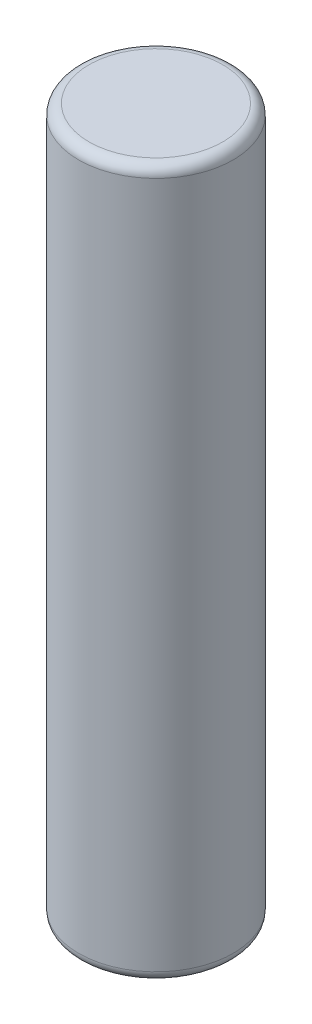
SolidWorks part; units mm, degrees
ref_plane "Alzado" through (0, 0, 0) normal (0, 0, 1) x (1, 0, 0)
ref_plane "Planta" through (0, 0, 0) normal (0, 1, 0) x (1, 0, 0)
ref_plane "Vista lateral" through (0, 0, 0) normal (1, 0, 0) x (0, 0, -1)
sketch "Croquis1" plane through (0, 0, 0) normal (0, 1, 0) x (1, 0, 0)
  circle A0 centre (0, 0) radius 7.425
  dimension "D1" = 14.85
extrude "Saliente-Extruir1" add sketch "Croquis1" along normal blind 68
fillet "Redondeo1" radius 1 2 edges at (0, 0, 7.425) (0, 68, 7.425)
